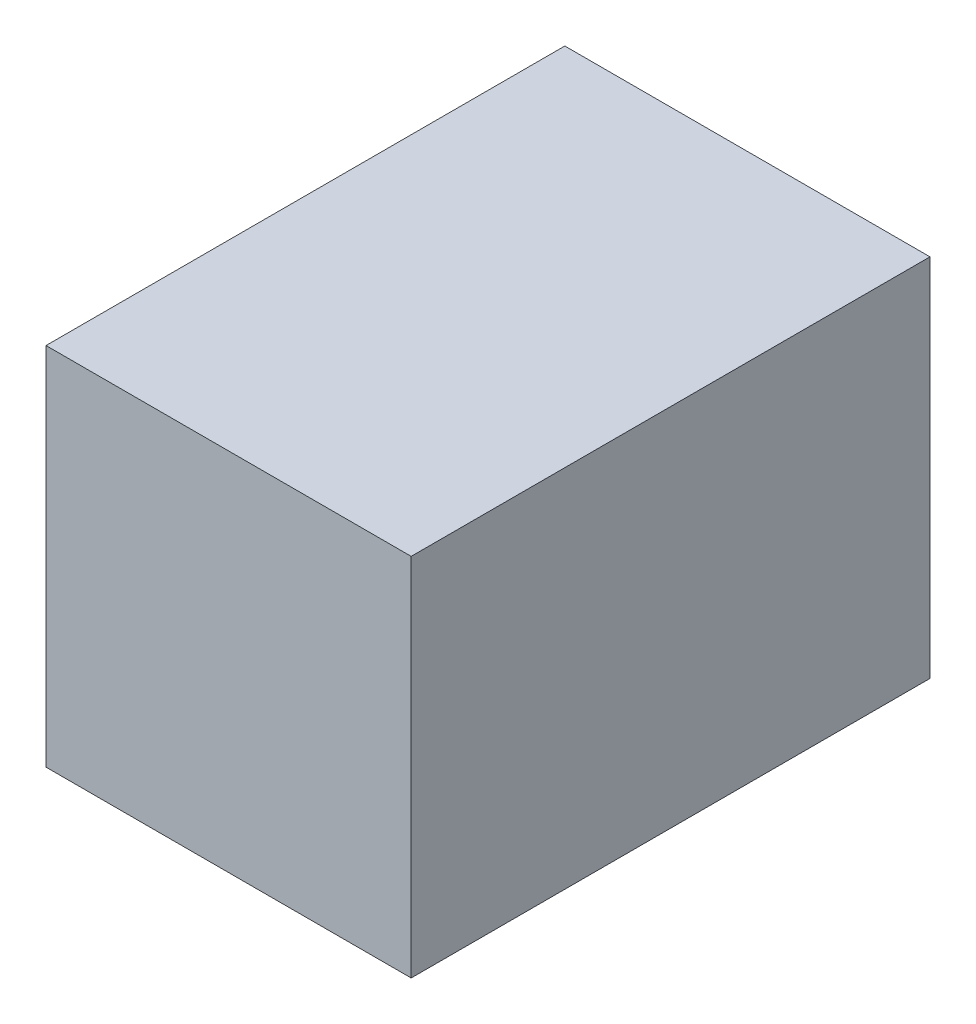
SolidWorks part; units mm, degrees
ref_plane "Front Plane" through (0, 0, 0) normal (0, 0, 1) x (1, 0, 0)
ref_plane "Top Plane" through (0, 0, 0) normal (0, 1, 0) x (1, 0, 0)
ref_plane "Right Plane" through (0, 0, 0) normal (1, 0, 0) x (0, 0, -1)
sketch "Sketch1" plane through (0, 0, 0) normal (0, 0, 1) x (1, 0, 0)
  line L1 (0, 0) -> (20, 0)
  line L2 (0, 0) -> (0, 20)
  line L3 (0, 20) -> (20, 20)
  line L4 (20, 0) -> (20, 20)
extrude "Boss-Extrude1" add sketch "Sketch1" along normal blind 28.4147
equation "\"A\" = atn(1)"
equation "\"D1@Boss-Extrude1\" = 20 + 10 * sin(1)"
